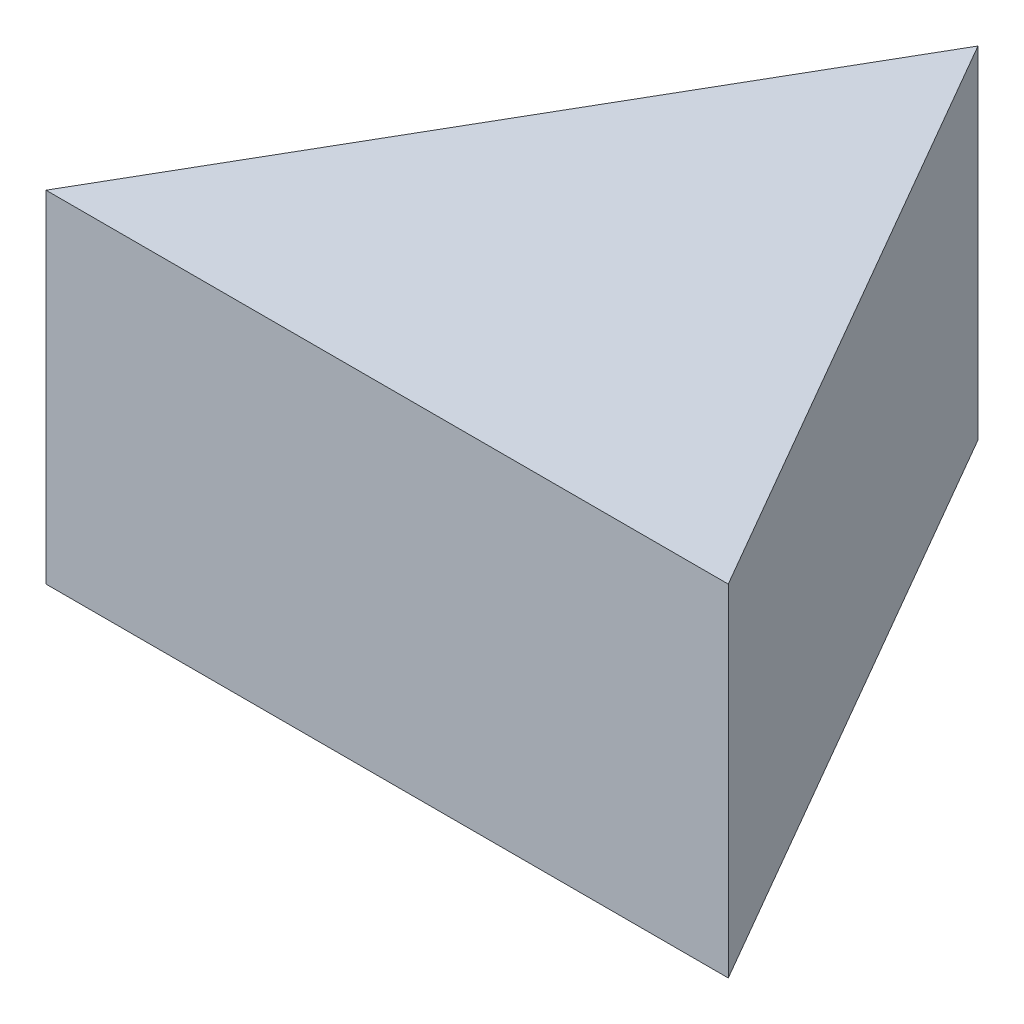
SolidWorks part; units mm, degrees
ref_plane "Přední rovina" through (0, 0, 0) normal (0, 0, 1) x (1, 0, 0)
ref_plane "Horní rovina" through (0, 0, 0) normal (0, 1, 0) x (1, 0, 0)
ref_plane "Pravá rovina" through (0, 0, 0) normal (1, 0, 0) x (0, 0, -1)
sketch "Sketch1" plane through (0, 0, 0) normal (0, 1, 0) x (1, 0, 0)
  line L0 (-20, 0) -> (20, 0)
  line L1 (20, 0) -> (0, 34.641)
  line L2 (0, 34.641) -> (0, 0) construction
  line L3 (-20, 0) -> (0, 34.641)
  point P4 (0, 0)
  point P5 (0, 0)
  point P6 (0, 16.8591)
  dimension "D1" = 60
  dimension "D2" = 20
extrude "Boss-Extrude1" add sketch "Sketch1" along normal blind 20 contours L2 L3 L0 | L1 L2 L0
equation "\"ěé\"=30"
